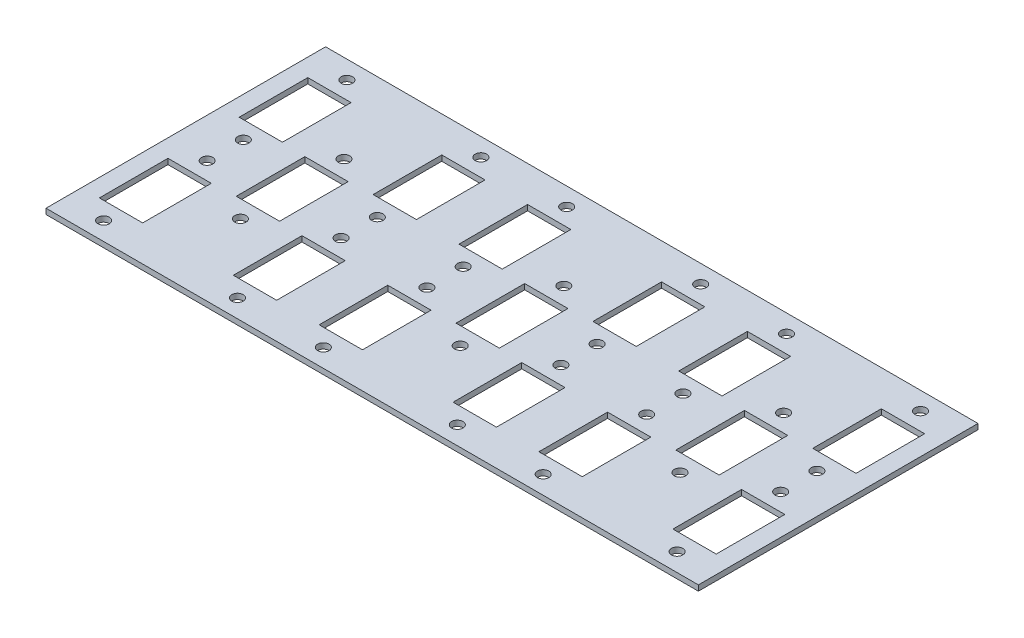
SolidWorks part; units mm, degrees
ref_plane "Front Plane" through (0, 0, 0) normal (0, 0, 1) x (1, 0, 0)
ref_plane "Top Plane" through (0, 0, 0) normal (0, 1, 0) x (1, 0, 0)
ref_plane "Right Plane" through (0, 0, 0) normal (1, 0, 0) x (0, 0, -1)
sketch "Solenoid Panel Cutouts" plane through (0, 0, 0) normal (0, 1, 0) x (1, 0, 0)
  line L0 (16.6437, 19.05) -> (4.8437, 19.05) construction
  line L1 (4.8437, 9.7) -> (16.6437, 9.7)
  line L2 (4.8437, 9.7) -> (4.8437, 28.4)
  line L3 (4.8437, 28.4) -> (16.6437, 28.4)
  line L4 (16.6437, 9.7) -> (16.6437, 28.4)
  line L5 (177.8, 0) -> (177.8, 76.2) construction
  line L6 (177.8, 0) -> (0, 0) construction
  line L7 (0, 0) -> (0, 76.2) construction
  line L8 (177.8, 76.2) -> (0, 76.2) construction
  line L9 (2.8437, 9.7) -> (4.8437, 4.9375) construction
  line L10 (18.6437, 9.7) -> (18.6437, 28.4) construction
  line L11 (2.8437, 9.7) -> (2.8437, 28.4) construction
  line L12 (2.8437, 28.4) -> (4.8437, 33.1625) construction
  line L13 (18.6437, 9.7) -> (16.6437, 4.9375) construction
  line L14 (18.6437, 28.4) -> (16.6437, 33.1625) construction
  line L15 (4.8437, 9.7) -> (4.8437, 28.4) construction
  line L16 (16.6437, 9.7) -> (16.6437, 28.4) construction
  line L17 (4.8437, 9.7) -> (4.8437, 28.4) construction
  line L18 (16.6437, 2.05) -> (4.8437, 2.05) construction
  line L19 (16.6437, 2.05) -> (16.6437, 4.9375) construction
  line L20 (16.6437, 36.05) -> (4.8437, 36.05) construction
  line L21 (4.8437, 2.05) -> (4.8437, 4.9375) construction
  line L22 (4.8437, 33.1625) -> (4.8437, 36.05) construction
  line L23 (16.6437, 33.1625) -> (16.6437, 36.05) construction
  line L24 (16.6437, 9.7) -> (16.6437, 28.4) construction
  line L25 (4.8437, 47.8) -> (16.6437, 47.8)
  line L26 (4.8437, 47.8) -> (4.8437, 66.5)
  line L27 (4.8437, 66.5) -> (16.6437, 66.5)
  line L28 (16.6437, 47.8) -> (16.6437, 66.5)
  line L29 (16.6437, 57.15) -> (4.8437, 57.15) construction
  line L30 (2.8437, 47.8) -> (4.8437, 43.0375) construction
  line L31 (18.6437, 47.8) -> (18.6437, 66.5) construction
  line L32 (2.8437, 47.8) -> (2.8437, 66.5) construction
  line L33 (2.8437, 66.5) -> (4.8437, 71.2625) construction
  line L34 (18.6437, 47.8) -> (16.6437, 43.0375) construction
  line L35 (18.6437, 66.5) -> (16.6437, 71.2625) construction
  line L36 (4.8437, 47.8) -> (4.8437, 66.5) construction
  line L37 (16.6437, 47.8) -> (16.6437, 66.5) construction
  line L38 (4.8437, 47.8) -> (4.8437, 66.5) construction
  line L39 (16.6437, 40.15) -> (4.8437, 40.15) construction
  line L40 (16.6437, 40.15) -> (16.6437, 43.0375) construction
  line L41 (16.6437, 74.15) -> (4.8437, 74.15) construction
  line L42 (4.8437, 40.15) -> (4.8437, 43.0375) construction
  line L43 (4.8437, 71.2625) -> (4.8437, 74.15) construction
  line L44 (16.6437, 71.2625) -> (16.6437, 74.15) construction
  line L45 (16.6437, 47.8) -> (16.6437, 66.5) construction
  line L46 (41.3562, 47.8) -> (53.1562, 47.8)
  line L47 (41.3562, 47.8) -> (41.3562, 66.5)
  line L48 (41.3562, 66.5) -> (53.1562, 66.5)
  line L49 (53.1562, 47.8) -> (53.1562, 66.5)
  line L50 (53.1562, 57.15) -> (41.3562, 57.15) construction
  line L51 (39.3562, 47.8) -> (41.3562, 43.0375) construction
  line L52 (55.1562, 47.8) -> (55.1562, 66.5) construction
  line L53 (39.3562, 47.8) -> (39.3562, 66.5) construction
  line L54 (39.3562, 66.5) -> (41.3562, 71.2625) construction
  line L55 (55.1562, 47.8) -> (53.1562, 43.0375) construction
  line L56 (55.1562, 66.5) -> (53.1562, 71.2625) construction
  line L57 (41.3562, 47.8) -> (41.3562, 66.5) construction
  line L58 (53.1562, 47.8) -> (53.1562, 66.5) construction
  line L59 (41.3562, 47.8) -> (41.3562, 66.5) construction
  line L60 (53.1562, 40.15) -> (41.3562, 40.15) construction
  line L61 (53.1562, 40.15) -> (53.1562, 43.0375) construction
  line L62 (53.1562, 74.15) -> (41.3562, 74.15) construction
  line L63 (41.3562, 40.15) -> (41.3562, 43.0375) construction
  line L64 (41.3562, 71.2625) -> (41.3562, 74.15) construction
  line L65 (53.1562, 71.2625) -> (53.1562, 74.15) construction
  line L66 (53.1562, 47.8) -> (53.1562, 66.5) construction
  line L67 (64.7437, 47.8) -> (76.5437, 47.8)
  line L68 (64.7437, 47.8) -> (64.7437, 66.5)
  line L69 (64.7437, 66.5) -> (76.5437, 66.5)
  line L70 (76.5437, 47.8) -> (76.5437, 66.5)
  line L71 (76.5437, 57.15) -> (64.7437, 57.15) construction
  line L72 (62.7437, 47.8) -> (64.7437, 43.0375) construction
  line L73 (78.5437, 47.8) -> (78.5437, 66.5) construction
  line L74 (62.7437, 47.8) -> (62.7437, 66.5) construction
  line L75 (62.7437, 66.5) -> (64.7437, 71.2625) construction
  line L76 (78.5437, 47.8) -> (76.5437, 43.0375) construction
  line L77 (78.5437, 66.5) -> (76.5437, 71.2625) construction
  line L78 (64.7437, 47.8) -> (64.7437, 66.5) construction
  line L79 (76.5437, 47.8) -> (76.5437, 66.5) construction
  line L80 (64.7437, 47.8) -> (64.7437, 66.5) construction
  line L81 (76.5437, 40.15) -> (64.7437, 40.15) construction
  line L82 (76.5437, 40.15) -> (76.5437, 43.0375) construction
  line L83 (76.5437, 74.15) -> (64.7437, 74.15) construction
  line L84 (64.7437, 40.15) -> (64.7437, 43.0375) construction
  line L85 (64.7437, 71.2625) -> (64.7437, 74.15) construction
  line L86 (76.5437, 71.2625) -> (76.5437, 74.15) construction
  line L87 (76.5437, 47.8) -> (76.5437, 66.5) construction
  line L88 (101.2562, 47.8) -> (113.0562, 47.8)
  line L89 (101.2562, 47.8) -> (101.2562, 66.5)
  line L90 (101.2562, 66.5) -> (113.0562, 66.5)
  line L91 (113.0562, 47.8) -> (113.0562, 66.5)
  line L92 (113.0562, 57.15) -> (101.2562, 57.15) construction
  line L93 (99.2562, 47.8) -> (101.2562, 43.0375) construction
  line L94 (115.0562, 47.8) -> (115.0562, 66.5) construction
  line L95 (99.2562, 47.8) -> (99.2562, 66.5) construction
  line L96 (99.2562, 66.5) -> (101.2562, 71.2625) construction
  line L97 (115.0562, 47.8) -> (113.0562, 43.0375) construction
  line L98 (115.0562, 66.5) -> (113.0562, 71.2625) construction
  line L99 (101.2562, 47.8) -> (101.2562, 66.5) construction
  line L100 (113.0562, 47.8) -> (113.0562, 66.5) construction
  line L101 (101.2562, 47.8) -> (101.2562, 66.5) construction
  line L102 (113.0562, 40.15) -> (101.2562, 40.15) construction
  line L103 (113.0562, 40.15) -> (113.0562, 43.0375) construction
  line L104 (113.0562, 74.15) -> (101.2562, 74.15) construction
  line L105 (101.2562, 40.15) -> (101.2562, 43.0375) construction
  line L106 (101.2562, 71.2625) -> (101.2562, 74.15) construction
  line L107 (113.0562, 71.2625) -> (113.0562, 74.15) construction
  line L108 (113.0562, 47.8) -> (113.0562, 66.5) construction
  line L109 (124.6437, 47.8) -> (136.4437, 47.8)
  line L110 (124.6437, 47.8) -> (124.6437, 66.5)
  line L111 (124.6437, 66.5) -> (136.4437, 66.5)
  line L112 (136.4437, 47.8) -> (136.4437, 66.5)
  line L113 (136.4437, 57.15) -> (124.6437, 57.15) construction
  line L114 (122.6437, 47.8) -> (124.6437, 43.0375) construction
  line L115 (138.4437, 47.8) -> (138.4437, 66.5) construction
  line L116 (122.6437, 47.8) -> (122.6437, 66.5) construction
  line L117 (122.6437, 66.5) -> (124.6437, 71.2625) construction
  line L118 (138.4437, 47.8) -> (136.4437, 43.0375) construction
  line L119 (138.4437, 66.5) -> (136.4437, 71.2625) construction
  line L120 (124.6437, 47.8) -> (124.6437, 66.5) construction
  line L121 (136.4437, 47.8) -> (136.4437, 66.5) construction
  line L122 (124.6437, 47.8) -> (124.6437, 66.5) construction
  line L123 (136.4437, 40.15) -> (124.6437, 40.15) construction
  line L124 (136.4437, 40.15) -> (136.4437, 43.0375) construction
  line L125 (136.4437, 74.15) -> (124.6437, 74.15) construction
  line L126 (124.6437, 40.15) -> (124.6437, 43.0375) construction
  line L127 (124.6437, 71.2625) -> (124.6437, 74.15) construction
  line L128 (136.4437, 71.2625) -> (136.4437, 74.15) construction
  line L129 (136.4437, 47.8) -> (136.4437, 66.5) construction
  line L130 (161.1562, 47.8) -> (172.9562, 47.8)
  line L131 (161.1562, 47.8) -> (161.1562, 66.5)
  line L132 (161.1562, 66.5) -> (172.9562, 66.5)
  line L133 (172.9562, 47.8) -> (172.9562, 66.5)
  line L134 (172.9562, 57.15) -> (161.1562, 57.15) construction
  line L135 (159.1562, 47.8) -> (161.1562, 43.0375) construction
  line L136 (174.9562, 47.8) -> (174.9562, 66.5) construction
  line L137 (159.1562, 47.8) -> (159.1562, 66.5) construction
  line L138 (159.1562, 66.5) -> (161.1562, 71.2625) construction
  line L139 (174.9562, 47.8) -> (172.9562, 43.0375) construction
  line L140 (174.9562, 66.5) -> (172.9562, 71.2625) construction
  line L141 (161.1562, 47.8) -> (161.1562, 66.5) construction
  line L142 (172.9562, 47.8) -> (172.9562, 66.5) construction
  line L143 (161.1562, 47.8) -> (161.1562, 66.5) construction
  line L144 (172.9562, 40.15) -> (161.1562, 40.15) construction
  line L145 (172.9562, 40.15) -> (172.9562, 43.0375) construction
  line L146 (172.9562, 74.15) -> (161.1562, 74.15) construction
  line L147 (161.1562, 40.15) -> (161.1562, 43.0375) construction
  line L148 (161.1562, 71.2625) -> (161.1562, 74.15) construction
  line L149 (172.9562, 71.2625) -> (172.9562, 74.15) construction
  line L150 (172.9562, 47.8) -> (172.9562, 66.5) construction
  line L151 (23.1, 28.75) -> (34.9, 28.75)
  line L152 (23.1, 28.75) -> (23.1, 47.45)
  line L153 (23.1, 47.45) -> (34.9, 47.45)
  line L154 (34.9, 28.75) -> (34.9, 47.45)
  line L155 (34.9, 38.1) -> (23.1, 38.1) construction
  line L156 (21.1, 28.75) -> (23.1, 23.9875) construction
  line L157 (36.9, 28.75) -> (36.9, 47.45) construction
  line L158 (21.1, 28.75) -> (21.1, 47.45) construction
  line L159 (21.1, 47.45) -> (23.1, 52.2125) construction
  line L160 (36.9, 28.75) -> (34.9, 23.9875) construction
  line L161 (36.9, 47.45) -> (34.9, 52.2125) construction
  line L162 (23.1, 28.75) -> (23.1, 47.45) construction
  line L163 (34.9, 28.75) -> (34.9, 47.45) construction
  line L164 (23.1, 28.75) -> (23.1, 47.45) construction
  line L165 (34.9, 21.1) -> (23.1, 21.1) construction
  line L166 (34.9, 21.1) -> (34.9, 23.9875) construction
  line L167 (34.9, 55.1) -> (23.1, 55.1) construction
  line L168 (23.1, 21.1) -> (23.1, 23.9875) construction
  line L169 (23.1, 52.2125) -> (23.1, 55.1) construction
  line L170 (34.9, 52.2125) -> (34.9, 55.1) construction
  line L171 (34.9, 28.75) -> (34.9, 47.45) construction
  line L172 (41.3562, 9.7) -> (53.1562, 9.7)
  line L173 (41.3562, 9.7) -> (41.3562, 28.4)
  line L174 (41.3562, 28.4) -> (53.1562, 28.4)
  line L175 (53.1562, 9.7) -> (53.1562, 28.4)
  line L176 (53.1562, 19.05) -> (41.3562, 19.05) construction
  line L177 (39.3562, 9.7) -> (41.3562, 4.9375) construction
  line L178 (55.1562, 9.7) -> (55.1562, 28.4) construction
  line L179 (39.3562, 9.7) -> (39.3562, 28.4) construction
  line L180 (39.3562, 28.4) -> (41.3562, 33.1625) construction
  line L181 (55.1562, 9.7) -> (53.1562, 4.9375) construction
  line L182 (55.1562, 28.4) -> (53.1562, 33.1625) construction
  line L183 (41.3562, 9.7) -> (41.3562, 28.4) construction
  line L184 (53.1562, 9.7) -> (53.1562, 28.4) construction
  line L185 (41.3562, 9.7) -> (41.3562, 28.4) construction
  line L186 (53.1562, 2.05) -> (41.3562, 2.05) construction
  line L187 (53.1562, 2.05) -> (53.1562, 4.9375) construction
  line L188 (53.1562, 36.05) -> (41.3562, 36.05) construction
  line L189 (41.3562, 2.05) -> (41.3562, 4.9375) construction
  line L190 (41.3562, 33.1625) -> (41.3562, 36.05) construction
  line L191 (53.1562, 33.1625) -> (53.1562, 36.05) construction
  line L192 (53.1562, 9.7) -> (53.1562, 28.4) construction
  line L193 (64.7437, 9.7) -> (76.5437, 9.7)
  line L194 (64.7437, 9.7) -> (64.7437, 28.4)
  line L195 (64.7437, 28.4) -> (76.5437, 28.4)
  line L196 (76.5437, 9.7) -> (76.5437, 28.4)
  line L197 (76.5437, 19.05) -> (64.7437, 19.05) construction
  line L198 (62.7437, 9.7) -> (64.7437, 4.9375) construction
  line L199 (78.5437, 9.7) -> (78.5437, 28.4) construction
  line L200 (62.7437, 9.7) -> (62.7437, 28.4) construction
  line L201 (62.7437, 28.4) -> (64.7437, 33.1625) construction
  line L202 (78.5437, 9.7) -> (76.5437, 4.9375) construction
  line L203 (78.5437, 28.4) -> (76.5437, 33.1625) construction
  line L204 (64.7437, 9.7) -> (64.7437, 28.4) construction
  line L205 (76.5437, 9.7) -> (76.5437, 28.4) construction
  line L206 (64.7437, 9.7) -> (64.7437, 28.4) construction
  line L207 (76.5437, 2.05) -> (64.7437, 2.05) construction
  line L208 (76.5437, 2.05) -> (76.5437, 4.9375) construction
  line L209 (76.5437, 36.05) -> (64.7437, 36.05) construction
  line L210 (64.7437, 2.05) -> (64.7437, 4.9375) construction
  line L211 (64.7437, 33.1625) -> (64.7437, 36.05) construction
  line L212 (76.5437, 33.1625) -> (76.5437, 36.05) construction
  line L213 (76.5437, 9.7) -> (76.5437, 28.4) construction
  line L214 (83, 28.75) -> (94.8, 28.75)
  line L215 (83, 28.75) -> (83, 47.45)
  line L216 (83, 47.45) -> (94.8, 47.45)
  line L217 (94.8, 28.75) -> (94.8, 47.45)
  line L218 (94.8, 38.1) -> (83, 38.1) construction
  line L219 (81, 28.75) -> (83, 23.9875) construction
  line L220 (96.8, 28.75) -> (96.8, 47.45) construction
  line L221 (81, 28.75) -> (81, 47.45) construction
  line L222 (81, 47.45) -> (83, 52.2125) construction
  line L223 (96.8, 28.75) -> (94.8, 23.9875) construction
  line L224 (96.8, 47.45) -> (94.8, 52.2125) construction
  line L225 (83, 28.75) -> (83, 47.45) construction
  line L226 (94.8, 28.75) -> (94.8, 47.45) construction
  line L227 (83, 28.75) -> (83, 47.45) construction
  line L228 (94.8, 21.1) -> (83, 21.1) construction
  line L229 (94.8, 21.1) -> (94.8, 23.9875) construction
  line L230 (94.8, 55.1) -> (83, 55.1) construction
  line L231 (83, 21.1) -> (83, 23.9875) construction
  line L232 (83, 52.2125) -> (83, 55.1) construction
  line L233 (94.8, 52.2125) -> (94.8, 55.1) construction
  line L234 (94.8, 28.75) -> (94.8, 47.45) construction
  line L235 (101.2562, 9.7) -> (113.0562, 9.7)
  line L236 (101.2562, 9.7) -> (101.2562, 28.4)
  line L237 (101.2562, 28.4) -> (113.0562, 28.4)
  line L238 (113.0562, 9.7) -> (113.0562, 28.4)
  line L239 (113.0562, 19.05) -> (101.2562, 19.05) construction
  line L240 (99.2562, 9.7) -> (101.2562, 4.9375) construction
  line L241 (115.0562, 9.7) -> (115.0562, 28.4) construction
  line L242 (99.2562, 9.7) -> (99.2562, 28.4) construction
  line L243 (99.2562, 28.4) -> (101.2562, 33.1625) construction
  line L244 (115.0562, 9.7) -> (113.0562, 4.9375) construction
  line L245 (115.0562, 28.4) -> (113.0562, 33.1625) construction
  line L246 (101.2562, 9.7) -> (101.2562, 28.4) construction
  line L247 (113.0562, 9.7) -> (113.0562, 28.4) construction
  line L248 (101.2562, 9.7) -> (101.2562, 28.4) construction
  line L249 (113.0562, 2.05) -> (101.2562, 2.05) construction
  line L250 (113.0562, 2.05) -> (113.0562, 4.9375) construction
  line L251 (113.0562, 36.05) -> (101.2562, 36.05) construction
  line L252 (101.2562, 2.05) -> (101.2562, 4.9375) construction
  line L253 (101.2562, 33.1625) -> (101.2562, 36.05) construction
  line L254 (113.0562, 33.1625) -> (113.0562, 36.05) construction
  line L255 (113.0562, 9.7) -> (113.0562, 28.4) construction
  line L256 (124.6437, 9.7) -> (136.4437, 9.7)
  line L257 (124.6437, 9.7) -> (124.6437, 28.4)
  line L258 (124.6437, 28.4) -> (136.4437, 28.4)
  line L259 (136.4437, 9.7) -> (136.4437, 28.4)
  line L260 (136.4437, 19.05) -> (124.6437, 19.05) construction
  line L261 (122.6437, 9.7) -> (124.6437, 4.9375) construction
  line L262 (138.4437, 9.7) -> (138.4437, 28.4) construction
  line L263 (122.6437, 9.7) -> (122.6437, 28.4) construction
  line L264 (122.6437, 28.4) -> (124.6437, 33.1625) construction
  line L265 (138.4437, 9.7) -> (136.4437, 4.9375) construction
  line L266 (138.4437, 28.4) -> (136.4437, 33.1625) construction
  line L267 (124.6437, 9.7) -> (124.6437, 28.4) construction
  line L268 (136.4437, 9.7) -> (136.4437, 28.4) construction
  line L269 (124.6437, 9.7) -> (124.6437, 28.4) construction
  line L270 (136.4437, 2.05) -> (124.6437, 2.05) construction
  line L271 (136.4437, 2.05) -> (136.4437, 4.9375) construction
  line L272 (136.4437, 36.05) -> (124.6437, 36.05) construction
  line L273 (124.6437, 2.05) -> (124.6437, 4.9375) construction
  line L274 (124.6437, 33.1625) -> (124.6437, 36.05) construction
  line L275 (136.4437, 33.1625) -> (136.4437, 36.05) construction
  line L276 (136.4437, 9.7) -> (136.4437, 28.4) construction
  line L277 (142.9, 28.75) -> (154.7, 28.75)
  line L278 (142.9, 28.75) -> (142.9, 47.45)
  line L279 (142.9, 47.45) -> (154.7, 47.45)
  line L280 (154.7, 28.75) -> (154.7, 47.45)
  line L281 (154.7, 38.1) -> (142.9, 38.1) construction
  line L282 (140.9, 28.75) -> (142.9, 23.9875) construction
  line L283 (156.7, 28.75) -> (156.7, 47.45) construction
  line L284 (140.9, 28.75) -> (140.9, 47.45) construction
  line L285 (140.9, 47.45) -> (142.9, 52.2125) construction
  line L286 (156.7, 28.75) -> (154.7, 23.9875) construction
  line L287 (156.7, 47.45) -> (154.7, 52.2125) construction
  line L288 (142.9, 28.75) -> (142.9, 47.45) construction
  line L289 (154.7, 28.75) -> (154.7, 47.45) construction
  line L290 (142.9, 28.75) -> (142.9, 47.45) construction
  line L291 (154.7, 21.1) -> (142.9, 21.1) construction
  line L292 (154.7, 21.1) -> (154.7, 23.9875) construction
  line L293 (154.7, 55.1) -> (142.9, 55.1) construction
  line L294 (142.9, 21.1) -> (142.9, 23.9875) construction
  line L295 (142.9, 52.2125) -> (142.9, 55.1) construction
  line L296 (154.7, 52.2125) -> (154.7, 55.1) construction
  line L297 (154.7, 28.75) -> (154.7, 47.45) construction
  line L298 (161.1562, 9.7) -> (172.9562, 9.7)
  line L299 (161.1562, 9.7) -> (161.1562, 28.4)
  line L300 (161.1562, 28.4) -> (172.9562, 28.4)
  line L301 (172.9562, 9.7) -> (172.9562, 28.4)
  line L302 (172.9562, 19.05) -> (161.1562, 19.05) construction
  line L303 (159.1562, 9.7) -> (161.1562, 4.9375) construction
  line L304 (174.9562, 9.7) -> (174.9562, 28.4) construction
  line L305 (159.1562, 9.7) -> (159.1562, 28.4) construction
  line L306 (159.1562, 28.4) -> (161.1562, 33.1625) construction
  line L307 (174.9562, 9.7) -> (172.9562, 4.9375) construction
  line L308 (174.9562, 28.4) -> (172.9562, 33.1625) construction
  line L309 (161.1562, 9.7) -> (161.1562, 28.4) construction
  line L310 (172.9562, 9.7) -> (172.9562, 28.4) construction
  line L311 (161.1562, 9.7) -> (161.1562, 28.4) construction
  line L312 (172.9562, 2.05) -> (161.1562, 2.05) construction
  line L313 (172.9562, 2.05) -> (172.9562, 4.9375) construction
  line L314 (172.9562, 36.05) -> (161.1562, 36.05) construction
  line L315 (161.1562, 2.05) -> (161.1562, 4.9375) construction
  line L316 (161.1562, 33.1625) -> (161.1562, 36.05) construction
  line L317 (172.9562, 33.1625) -> (172.9562, 36.05) construction
  line L318 (172.9562, 9.7) -> (172.9562, 28.4) construction
  circle A0 centre (10.7437, 33.1625) radius 1.55
  circle A1 centre (10.7437, 4.9375) radius 1.55
  circle A2 centre (10.7437, 71.2625) radius 1.55
  circle A3 centre (10.7437, 43.0375) radius 1.55
  circle A4 centre (47.2562, 71.2625) radius 1.55
  circle A5 centre (47.2562, 43.0375) radius 1.55
  circle A6 centre (70.6437, 71.2625) radius 1.55
  circle A7 centre (70.6437, 43.0375) radius 1.55
  circle A8 centre (107.1562, 71.2625) radius 1.55
  circle A9 centre (107.1562, 43.0375) radius 1.55
  circle A10 centre (130.5437, 71.2625) radius 1.55
  circle A11 centre (130.5437, 43.0375) radius 1.55
  circle A12 centre (167.0562, 71.2625) radius 1.55
  circle A13 centre (167.0562, 43.0375) radius 1.55
  circle A14 centre (29, 52.2125) radius 1.55
  circle A15 centre (29, 23.9875) radius 1.55
  circle A16 centre (47.2562, 33.1625) radius 1.55
  circle A17 centre (47.2562, 4.9375) radius 1.55
  circle A18 centre (70.6437, 33.1625) radius 1.55
  circle A19 centre (70.6437, 4.9375) radius 1.55
  circle A20 centre (88.9, 52.2125) radius 1.55
  circle A21 centre (88.9, 23.9875) radius 1.55
  circle A22 centre (107.1562, 33.1625) radius 1.55
  circle A23 centre (107.1562, 4.9375) radius 1.55
  circle A24 centre (130.5437, 33.1625) radius 1.55
  circle A25 centre (130.5437, 4.9375) radius 1.55
  circle A26 centre (148.8, 52.2125) radius 1.55
  circle A27 centre (148.8, 23.9875) radius 1.55
  circle A28 centre (167.0562, 33.1625) radius 1.55
  circle A29 centre (167.0562, 4.9375) radius 1.55
  point P0 (10.7437, 19.05)
  point P10 (10.7437, 19.05)
  point P12 (10.7437, 57.15)
  point P26 (10.7437, 57.15)
  point P28 (10.7437, 57.15)
  point P29 (10.7437, 57.15)
  point P33 (10.7437, 57.15)
  point P43 (47.2562, 57.15)
  point P53 (47.2562, 57.15)
  point P55 (47.2562, 57.15)
  point P56 (47.2562, 57.15)
  point P60 (47.2562, 57.15)
  point P70 (70.6437, 57.15)
  point P80 (70.6437, 57.15)
  point P82 (70.6437, 57.15)
  point P83 (70.6437, 57.15)
  point P87 (70.6437, 57.15)
  point P97 (10.7437, 19.05)
  point P98 (10.7437, 19.05)
  point P102 (10.7437, 19.05)
  point P112 (107.1562, 57.15)
  point P122 (107.1562, 57.15)
  point P124 (107.1562, 57.15)
  point P125 (107.1562, 57.15)
  point P129 (107.1562, 57.15)
  point P139 (130.5437, 57.15)
  point P149 (130.5437, 57.15)
  point P151 (130.5437, 57.15)
  point P152 (130.5437, 57.15)
  point P156 (130.5437, 57.15)
  point P166 (167.0562, 57.15)
  point P176 (167.0562, 57.15)
  point P178 (167.0562, 57.15)
  point P179 (167.0562, 57.15)
  point P183 (167.0562, 57.15)
  point P193 (29, 38.1)
  point P203 (29, 38.1)
  point P205 (29, 38.1)
  point P206 (29, 38.1)
  point P210 (29, 38.1)
  point P220 (47.2562, 19.05)
  point P230 (47.2562, 19.05)
  point P232 (47.2562, 19.05)
  point P233 (47.2562, 19.05)
  point P237 (47.2562, 19.05)
  point P247 (70.6437, 19.05)
  point P257 (70.6437, 19.05)
  point P259 (70.6437, 19.05)
  point P260 (70.6437, 19.05)
  point P264 (70.6437, 19.05)
  point P274 (88.9, 38.1)
  point P284 (88.9, 38.1)
  point P286 (88.9, 38.1)
  point P287 (88.9, 38.1)
  point P291 (88.9, 38.1)
  point P301 (107.1562, 19.05)
  point P311 (107.1562, 19.05)
  point P313 (107.1562, 19.05)
  point P314 (107.1562, 19.05)
  point P318 (107.1562, 19.05)
  point P328 (130.5437, 19.05)
  point P338 (130.5437, 19.05)
  point P340 (130.5437, 19.05)
  point P341 (130.5437, 19.05)
  point P345 (130.5437, 19.05)
  point P355 (148.8, 38.1)
  point P365 (148.8, 38.1)
  point P367 (148.8, 38.1)
  point P368 (148.8, 38.1)
  point P372 (148.8, 38.1)
  point P382 (167.0562, 19.05)
  point P392 (167.0562, 19.05)
  point P394 (167.0562, 19.05)
  point P395 (167.0562, 19.05)
  point P399 (167.0562, 19.05)
  point P409 (0, 0)
  dimension "D1" = 18.7
  dimension "D2" = 4.7625
  dimension "D3" = 177.8
  dimension "D4" = 76.2
  dimension "D5" = 15.8
  dimension "D6" = 18.7
  dimension "D7" = 34
  dimension "D8" = 4.7625
sketch "Sketch4" plane through (0, 0, 0) normal (0, 1, 0) x (1, 0, 0)
  line L1 (0, 0) -> (177.8, 0)
  line L2 (0, 0) -> (0, 76.2)
  line L3 (0, 76.2) -> (177.8, 76.2)
  line L4 (177.8, 0) -> (177.8, 76.2)
extrude "Boss-Extrude3" add sketch "Sketch4" along normal blind 1.5
extrude "Solenoid Panel Cutout" cut sketch "Solenoid Panel Cutouts" along normal up to surface (1.5 mm away) up to face at (88.9, 1.5, -38.1)
